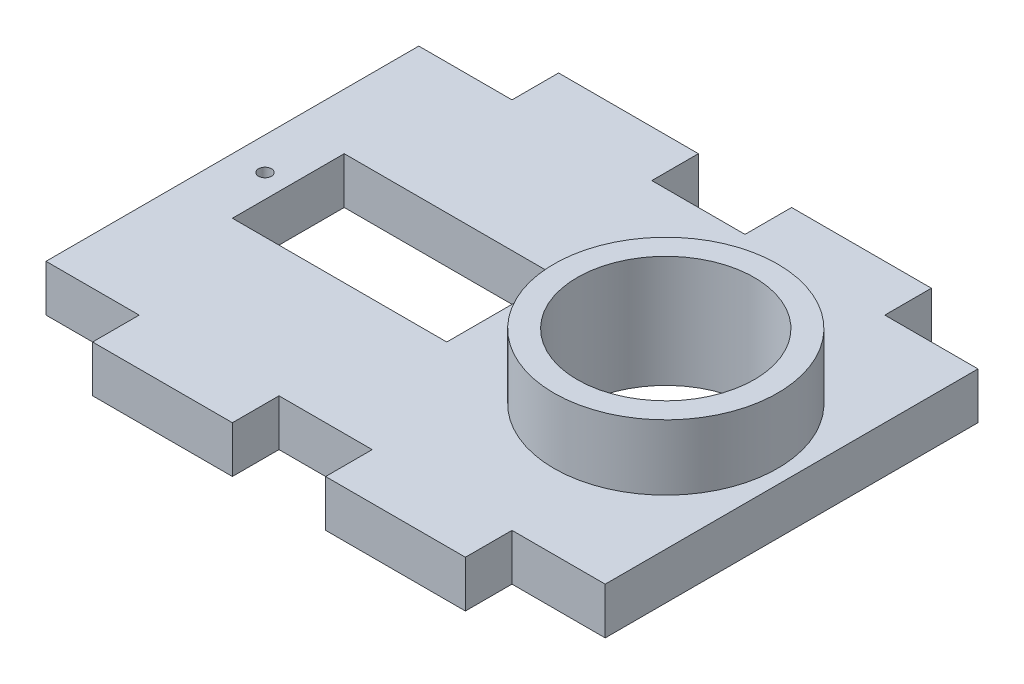
SolidWorks part; units mm, degrees
ref_plane "Front Plane" through (0, 0, 0) normal (0, 0, 1) x (1, 0, 0)
ref_plane "Top Plane" through (0, 0, 0) normal (0, 1, 0) x (1, 0, 0)
ref_plane "Right Plane" through (0, 0, 0) normal (1, 0, 0) x (0, 0, -1)
sketch "Sketch1" plane through (0, 0, 0) normal (0, 1, 0) x (1, 0, 0)
  line L0 (7.5, 20) -> (17.5, 20)
  line L1 (-17.5, -20) -> (-7.5, -20)
  line L2 (-17.5, -20) -> (-17.5, 20)
  line L3 (-17.5, 20) -> (-7.5, 20)
  line L4 (42.5, -20) -> (42.5, 20)
  line L5 (32.5, 20) -> (42.5, 20)
  line L7 (-11.5, -6) -> (11.5, -6)
  line L8 (-11.5, -6) -> (-11.5, 6)
  line L9 (-11.5, 6) -> (11.5, 6)
  line L10 (11.5, -6) -> (11.5, 6)
  line L11 (32.5, 20) -> (32.5, 25)
  line L12 (32.5, 25) -> (17.5, 25)
  line L14 (-7.5, 20) -> (-7.5, 25)
  line L15 (-7.5, 25) -> (7.5, 25)
  line L16 (7.5, 20) -> (7.5, 25)
  line L18 (-7.5, -20) -> (-7.5, -25)
  line L19 (-7.5, -25) -> (7.5, -25)
  line L20 (7.5, -20) -> (7.5, -25)
  line L21 (7.5, -20) -> (17.5, -20)
  line L22 (17.5, 20) -> (17.5, 25)
  line L24 (32.5, -20) -> (32.5, -25)
  line L25 (32.5, -25) -> (17.5, -25)
  line L26 (17.5, -20) -> (17.5, -25)
  line L27 (32.5, -20) -> (42.5, -20)
  circle A0 centre (-14, 0) radius 0.7
  circle A1 centre (14, 0) radius 0.7
  circle A2 centre (29, 0) radius 9.5
  point P0 (0, 0)
  point P10 (0, 0)
  dimension "D6" = 1.4
  dimension "D7" = 1.4
  dimension "D15" = 19
  dimension "D17" = 10
  dimension "D1" = 40
  dimension "D2" = 28
  dimension "D3" = 14
  dimension "D4" = 12
  dimension "D5" = 23
  dimension "D8" = 60
  dimension "D9" = 15
  dimension "D10" = 10
  dimension "D11" = 5
  dimension "D12" = 5
  dimension "D13" = 20
  dimension "D14" = 10
  dimension "D16" = 15
  dimension "D18" = 15
  dimension "D19" = 10
extrude "Boss-Extrude1" add sketch "Sketch1" along normal blind 5
sketch "Sketch2" plane through (0, 5, 0) normal (0, 1, 0) x (1, 0, 0)
  circle A0 centre (29, 0) radius 12
  circle A1 centre (29, 0) radius 9.5 construction
  circle A2 centre (29, 0) radius 9.5
  dimension "D1" = 2.5
extrude "Boss-Extrude2" add sketch "Sketch2" along normal blind 7
sketch "Sketch3" plane through (0, 0, 0) normal (0, -1, 0) x (1, 0, 0)
  circle A2 centre (29, 0) radius 9.5
  circle A3 centre (29, 0) radius 3.5
